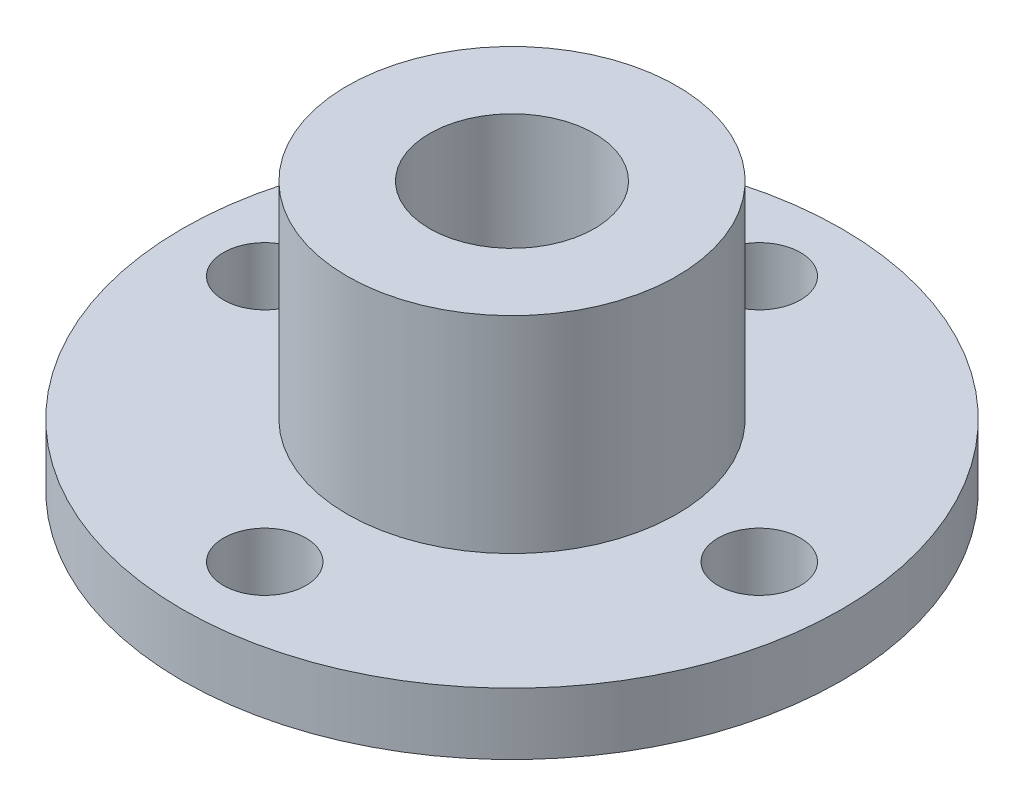
SolidWorks part; units mm, degrees
ref_plane "前视基准面" through (0, 0, 0) normal (0, 0, 1) x (1, 0, 0)
ref_plane "上视基准面" through (0, 0, 0) normal (0, 1, 0) x (1, 0, 0)
ref_plane "右视基准面" through (0, 0, 0) normal (1, 0, 0) x (0, 0, -1)
other "Configuration Table"
sketch "草图1" plane through (0, 0, 0) normal (0, 1, 0) x (1, 0, 0)
  line L0 (0, 16) -> (0, -16) construction
  line L1 (-16, 0) -> (16, 0) construction
  line L2 (0, 0) -> (11.3137, 11.3137) construction
  circle A0 centre (0, 0) radius 16
  circle A1 centre (-12, 0) radius 2
  circle A2 centre (12, 0) radius 2
  circle A3 centre (0, -12) radius 2
  circle A4 centre (0, 12) radius 2
  dimension "D1" = 32
  dimension "D3" = 4
  dimension "D2" = 12
  dimension "D4" = 45
extrude "凸台-拉伸1" add sketch "草图1" along normal blind 3 contours A0
sketch "草图2" plane through (0, 3, 0) normal (0, 1, 0) x (1, 0, 0)
  circle A0 centre (0, 0) radius 8
  dimension "D1" = 16
extrude "凸台-拉伸2" add sketch "草图2" along normal blind 10
sketch "草图3" plane through (0, 13, 0) normal (0, 1, 0) x (1, 0, 0)
  circle A0 centre (0, 0) radius 4
  dimension "D1" = 8
extrude "切除-拉伸1" cut sketch "草图3" against normal through all
equation "\"3mian\"=10"
